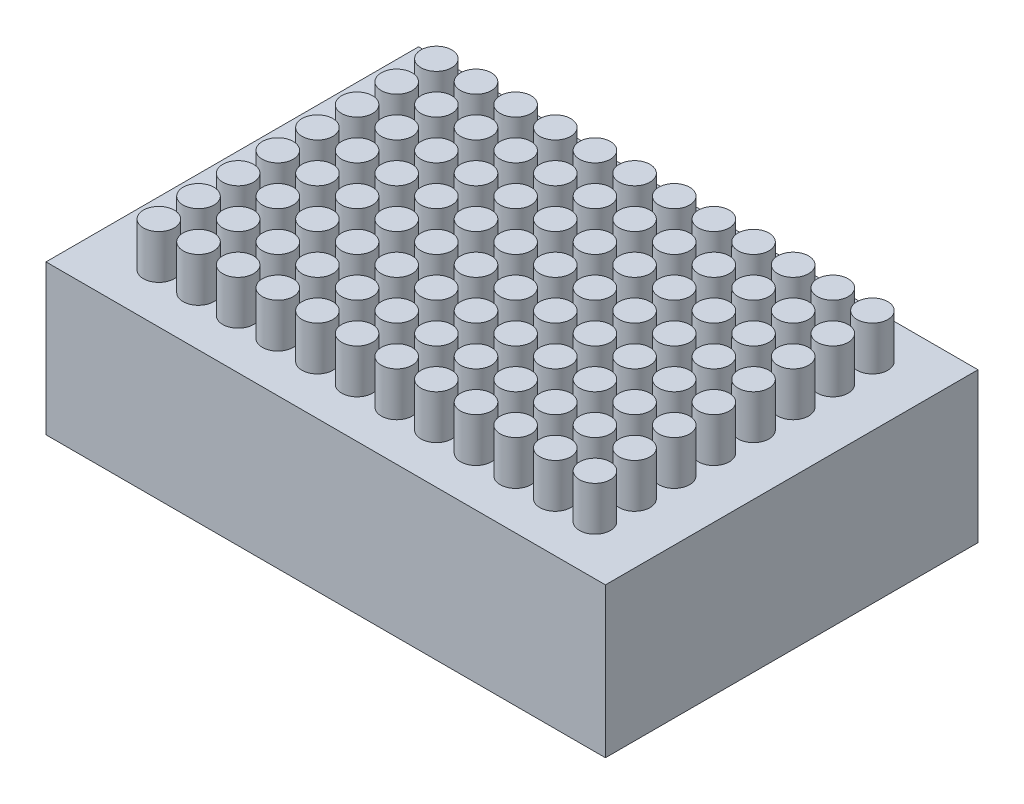
SolidWorks part; units mm, degrees
ref_plane "Front Plane" through (0, 0, 0) normal (0, 0, 1) x (1, 0, 0)
ref_plane "Top Plane" through (0, 0, 0) normal (0, 1, 0) x (1, 0, 0)
ref_plane "Right Plane" through (0, 0, 0) normal (1, 0, 0) x (0, 0, -1)
sketch "Sketch1" plane through (0, 0, 0) normal (0, 1, 0) x (1, 0, 0)
  line L0 (63.5, 84.582) -> (63.5, 0) construction
  line L1 (0, 0) -> (127, 0)
  line L2 (0, 0) -> (0, 84.582)
  line L3 (0, 84.582) -> (127, 84.582)
  line L4 (127, 0) -> (127, 84.582)
  line L5 (127, 42.291) -> (0, 42.291) construction
  circle A0 centre (59.38, 47.24) radius 3.5 construction
  circle A1 centre (14.38, 37.342) radius 3.5 construction
  circle A2 centre (23.38, 37.342) radius 3.5 construction
  circle A3 centre (32.38, 37.342) radius 3.5 construction
  circle A4 centre (50.38, 47.24) radius 3.5 construction
  circle A5 centre (41.38, 47.24) radius 3.5 construction
  circle A6 centre (32.38, 47.24) radius 3.5 construction
  circle A7 centre (23.38, 47.24) radius 3.5 construction
  circle A8 centre (14.38, 47.24) radius 3.5 construction
  circle A9 centre (41.38, 37.342) radius 3.5 construction
  circle A10 centre (50.38, 37.342) radius 3.5 construction
  circle A11 centre (59.38, 37.342) radius 3.5 construction
  circle A12 centre (67.62, 37.342) radius 3.5 construction
  circle A13 centre (76.62, 37.342) radius 3.5 construction
  circle A14 centre (85.62, 37.342) radius 3.5 construction
  circle A15 centre (112.62, 47.24) radius 3.5 construction
  circle A16 centre (103.62, 47.24) radius 3.5 construction
  circle A17 centre (94.62, 47.24) radius 3.5 construction
  circle A18 centre (85.62, 47.24) radius 3.5 construction
  circle A19 centre (76.62, 47.24) radius 3.5 construction
  circle A20 centre (94.62, 37.342) radius 3.5 construction
  circle A21 centre (103.62, 37.342) radius 3.5 construction
  circle A22 centre (112.62, 37.342) radius 3.5 construction
  circle A23 centre (67.62, 47.24) radius 3.5 construction
  circle A24 centre (59.38, 56.24) radius 3.5 construction
  circle A25 centre (50.38, 56.24) radius 3.5 construction
  circle A26 centre (41.38, 56.24) radius 3.5 construction
  circle A27 centre (32.38, 56.24) radius 3.5 construction
  circle A28 centre (23.38, 56.24) radius 3.5 construction
  circle A29 centre (14.38, 56.24) radius 3.5 construction
  circle A30 centre (112.62, 56.24) radius 3.5 construction
  circle A31 centre (103.62, 56.24) radius 3.5 construction
  circle A32 centre (94.62, 56.24) radius 3.5 construction
  circle A33 centre (85.62, 56.24) radius 3.5 construction
  circle A34 centre (76.62, 56.24) radius 3.5 construction
  circle A35 centre (67.62, 56.24) radius 3.5 construction
  circle A36 centre (59.38, 65.24) radius 3.5 construction
  circle A37 centre (50.38, 65.24) radius 3.5 construction
  circle A38 centre (41.38, 65.24) radius 3.5 construction
  circle A39 centre (32.38, 65.24) radius 3.5 construction
  circle A40 centre (23.38, 65.24) radius 3.5 construction
  circle A41 centre (14.38, 65.24) radius 3.5 construction
  circle A42 centre (112.62, 65.24) radius 3.5 construction
  circle A43 centre (103.62, 65.24) radius 3.5 construction
  circle A44 centre (94.62, 65.24) radius 3.5 construction
  circle A45 centre (85.62, 65.24) radius 3.5 construction
  circle A46 centre (76.62, 65.24) radius 3.5 construction
  circle A47 centre (67.62, 65.24) radius 3.5 construction
  circle A48 centre (59.38, 74.24) radius 3.5 construction
  circle A49 centre (50.38, 74.24) radius 3.5 construction
  circle A50 centre (41.38, 74.24) radius 3.5 construction
  circle A51 centre (32.38, 74.24) radius 3.5 construction
  circle A52 centre (23.38, 74.24) radius 3.5 construction
  circle A53 centre (14.38, 74.24) radius 3.5 construction
  circle A54 centre (112.62, 74.24) radius 3.5 construction
  circle A55 centre (103.62, 74.24) radius 3.5 construction
  circle A56 centre (94.62, 74.24) radius 3.5 construction
  circle A57 centre (85.62, 74.24) radius 3.5 construction
  circle A58 centre (76.62, 74.24) radius 3.5 construction
  circle A59 centre (67.62, 74.24) radius 3.5 construction
  circle A60 centre (14.38, 28.342) radius 3.5 construction
  circle A61 centre (23.38, 28.342) radius 3.5 construction
  circle A62 centre (32.38, 28.342) radius 3.5 construction
  circle A63 centre (41.38, 28.342) radius 3.5 construction
  circle A64 centre (50.38, 28.342) radius 3.5 construction
  circle A65 centre (59.38, 28.342) radius 3.5 construction
  circle A66 centre (67.62, 28.342) radius 3.5 construction
  circle A67 centre (76.62, 28.342) radius 3.5 construction
  circle A68 centre (85.62, 28.342) radius 3.5 construction
  circle A69 centre (94.62, 28.342) radius 3.5 construction
  circle A70 centre (103.62, 28.342) radius 3.5 construction
  circle A71 centre (112.62, 28.342) radius 3.5 construction
  circle A72 centre (14.38, 19.342) radius 3.5 construction
  circle A73 centre (23.38, 19.342) radius 3.5 construction
  circle A74 centre (32.38, 19.342) radius 3.5 construction
  circle A75 centre (41.38, 19.342) radius 3.5 construction
  circle A76 centre (50.38, 19.342) radius 3.5 construction
  circle A77 centre (59.38, 19.342) radius 3.5 construction
  circle A78 centre (67.62, 19.342) radius 3.5 construction
  circle A79 centre (76.62, 19.342) radius 3.5 construction
  circle A80 centre (85.62, 19.342) radius 3.5 construction
  circle A81 centre (94.62, 19.342) radius 3.5 construction
  circle A82 centre (103.62, 19.342) radius 3.5 construction
  circle A83 centre (112.62, 19.342) radius 3.5 construction
  circle A84 centre (14.38, 10.342) radius 3.5 construction
  circle A85 centre (23.38, 10.342) radius 3.5 construction
  circle A86 centre (32.38, 10.342) radius 3.5 construction
  circle A87 centre (41.38, 10.342) radius 3.5 construction
  circle A88 centre (50.38, 10.342) radius 3.5 construction
  circle A89 centre (59.38, 10.342) radius 3.5 construction
  circle A90 centre (67.62, 10.342) radius 3.5 construction
  circle A91 centre (76.62, 10.342) radius 3.5 construction
  circle A92 centre (85.62, 10.342) radius 3.5 construction
  circle A93 centre (94.62, 10.342) radius 3.5 construction
  circle A94 centre (103.62, 10.342) radius 3.5 construction
  circle A95 centre (112.62, 10.342) radius 3.5 construction
  dimension "D5" = 6
  dimension "D1" = 84.582
  dimension "D2" = 127
  dimension "D3" = 4
  dimension "D4" = 4
extrude "Boss-Extrude1" add sketch "Sketch1" along normal blind 34
sketch "Sketch4" plane through (0, 34, 0) normal (0, 1, 0) x (1, 0, 0)
  circle A0 centre (104.38, 11.24) radius 3.5
  circle A1 centre (95.38, 11.24) radius 3.5
  circle A2 centre (86.38, 11.24) radius 3.5
  circle A3 centre (77.38, 11.24) radius 3.5
  circle A4 centre (68.38, 11.24) radius 3.5
  circle A5 centre (59.38, 11.24) radius 3.5
  circle A6 centre (50.38, 11.24) radius 3.5
  circle A7 centre (41.38, 11.24) radius 3.5
  circle A8 centre (32.38, 11.24) radius 3.5
  circle A9 centre (23.38, 11.24) radius 3.5
  circle A10 centre (14.38, 11.24) radius 3.5
  circle A11 centre (113.38, 20.24) radius 3.5
  circle A12 centre (104.38, 20.24) radius 3.5
  circle A13 centre (95.38, 20.24) radius 3.5
  circle A14 centre (86.38, 20.24) radius 3.5
  circle A15 centre (77.38, 20.24) radius 3.5
  circle A16 centre (68.38, 20.24) radius 3.5
  circle A17 centre (59.38, 20.24) radius 3.5
  circle A18 centre (50.38, 20.24) radius 3.5
  circle A19 centre (41.38, 20.24) radius 3.5
  circle A20 centre (32.38, 20.24) radius 3.5
  circle A21 centre (23.38, 20.24) radius 3.5
  circle A22 centre (14.38, 20.24) radius 3.5
  circle A23 centre (113.38, 29.24) radius 3.5
  circle A24 centre (104.38, 29.24) radius 3.5
  circle A25 centre (95.38, 29.24) radius 3.5
  circle A26 centre (113.38, 11.24) radius 3.5
  circle A27 centre (86.38, 29.24) radius 3.5
  circle A28 centre (77.38, 29.24) radius 3.5
  circle A29 centre (68.38, 29.24) radius 3.5
  circle A30 centre (59.38, 29.24) radius 3.5
  circle A31 centre (50.38, 29.24) radius 3.5
  circle A32 centre (41.38, 29.24) radius 3.5
  circle A33 centre (32.38, 29.24) radius 3.5
  circle A34 centre (23.38, 29.24) radius 3.5
  circle A35 centre (14.38, 29.24) radius 3.5
  circle A36 centre (113.38, 38.24) radius 3.5
  circle A37 centre (104.38, 38.24) radius 3.5
  circle A38 centre (95.38, 38.24) radius 3.5
  circle A39 centre (86.38, 38.24) radius 3.5
  circle A40 centre (77.38, 38.24) radius 3.5
  circle A41 centre (68.38, 38.24) radius 3.5
  circle A42 centre (59.38, 38.24) radius 3.5
  circle A43 centre (50.38, 38.24) radius 3.5
  circle A44 centre (41.38, 38.24) radius 3.5
  circle A45 centre (32.38, 38.24) radius 3.5
  circle A46 centre (23.38, 38.24) radius 3.5
  circle A47 centre (14.38, 38.24) radius 3.5
  circle A48 centre (113.38, 47.24) radius 3.5
  circle A49 centre (104.38, 47.24) radius 3.5
  circle A50 centre (95.38, 47.24) radius 3.5
  circle A51 centre (86.38, 47.24) radius 3.5
  circle A52 centre (77.38, 47.24) radius 3.5
  circle A53 centre (68.38, 47.24) radius 3.5
  circle A54 centre (59.38, 47.24) radius 3.5
  circle A55 centre (50.38, 47.24) radius 3.5
  circle A56 centre (41.38, 47.24) radius 3.5
  circle A57 centre (32.38, 47.24) radius 3.5
  circle A58 centre (23.38, 47.24) radius 3.5
  circle A59 centre (14.38, 47.24) radius 3.5
  circle A60 centre (113.38, 56.24) radius 3.5
  circle A61 centre (104.38, 56.24) radius 3.5
  circle A62 centre (95.38, 56.24) radius 3.5
  circle A63 centre (86.38, 56.24) radius 3.5
  circle A64 centre (77.38, 56.24) radius 3.5
  circle A65 centre (68.38, 56.24) radius 3.5
  circle A66 centre (59.38, 56.24) radius 3.5
  circle A67 centre (50.38, 56.24) radius 3.5
  circle A68 centre (41.38, 56.24) radius 3.5
  circle A69 centre (32.38, 56.24) radius 3.5
  circle A70 centre (23.38, 56.24) radius 3.5
  circle A71 centre (14.38, 56.24) radius 3.5
  circle A72 centre (113.38, 65.24) radius 3.5
  circle A73 centre (104.38, 65.24) radius 3.5
  circle A74 centre (95.38, 65.24) radius 3.5
  circle A75 centre (86.38, 65.24) radius 3.5
  circle A76 centre (77.38, 65.24) radius 3.5
  circle A77 centre (68.38, 65.24) radius 3.5
  circle A78 centre (59.38, 65.24) radius 3.5
  circle A79 centre (50.38, 65.24) radius 3.5
  circle A80 centre (41.38, 65.24) radius 3.5
  circle A81 centre (32.38, 65.24) radius 3.5
  circle A82 centre (23.38, 65.24) radius 3.5
  circle A83 centre (14.38, 65.24) radius 3.5
  circle A84 centre (113.38, 74.24) radius 3.5
  circle A85 centre (104.38, 74.24) radius 3.5
  circle A86 centre (95.38, 74.24) radius 3.5
  circle A87 centre (86.38, 74.24) radius 3.5
  circle A88 centre (77.38, 74.24) radius 3.5
  circle A89 centre (68.38, 74.24) radius 3.5
  circle A90 centre (59.38, 74.24) radius 3.5
  circle A91 centre (50.38, 74.24) radius 3.5
  circle A92 centre (41.38, 74.24) radius 3.5
  circle A93 centre (32.38, 74.24) radius 3.5
  circle A94 centre (23.38, 74.24) radius 3.5
  circle A95 centre (14.38, 74.24) radius 3.5
  dimension "D2" = 4
extrude "Boss-Extrude2" add sketch "Sketch4" along normal blind 10
